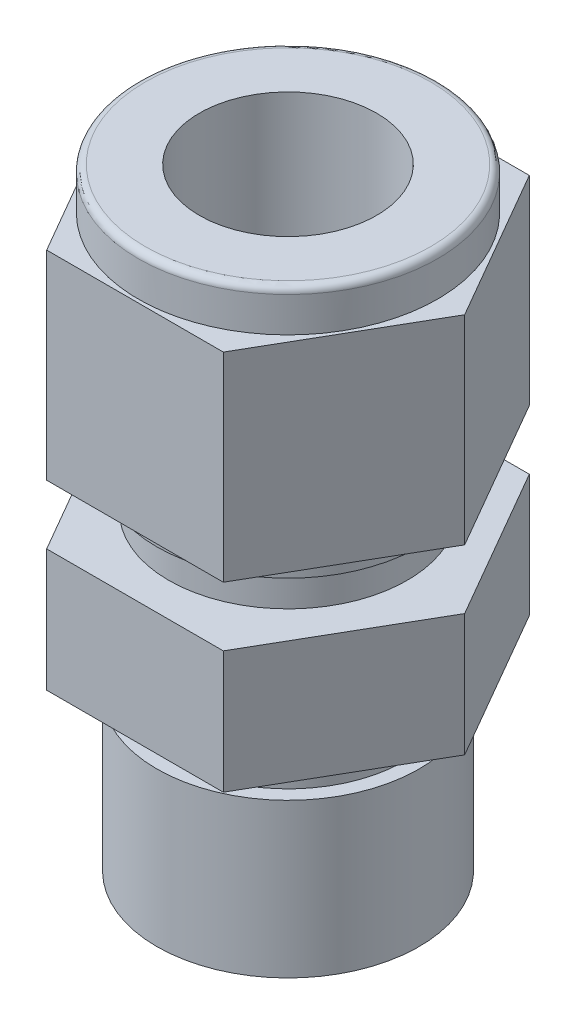
SolidWorks part; units mm, degrees
ref_plane "Front Plane" through (0, 0, 0) normal (0, 0, 1) x (1, 0, 0)
ref_plane "Top Plane" through (0, 0, 0) normal (0, 1, 0) x (1, 0, 0)
ref_plane "Right Plane" through (0, 0, 0) normal (1, 0, 0) x (0, 0, -1)
sketch "Sketch1" plane through (0, 0, 0) normal (0, 1, 0) x (1, 0, 0)
  circle A0 centre (0, 0) radius 9.525
  dimension "D1" = 19.05
extrude "Boss-Extrude1" add sketch "Sketch1" along normal blind 11.176
sketch "Sketch3" plane through (0, 11.176, 0) normal (0, 1, 0) x (1, 0, 0)
  circle A0 centre (0, 0) radius 8.509
  dimension "D1" = 17.018
extrude "Boss-Extrude3" add sketch "Sketch3" along normal blind 2.54
sketch "Sketch4" plane through (0, 13.716, 0) normal (0, 1, 0) x (1, 0, 0)
  line L1 (12.8316, 0) -> (6.4158, 11.1125)
  line L2 (6.4158, 11.1125) -> (-6.4158, 11.1125)
  line L3 (-6.4158, 11.1125) -> (-12.8316, 0)
  line L4 (-12.8316, 0) -> (-6.4158, -11.1125)
  line L5 (-6.4158, -11.1125) -> (6.4158, -11.1125)
  line L6 (6.4158, -11.1125) -> (12.8316, 0)
  circle A0 centre (0, 0) radius 11.1125 construction
  dimension "D1" = 22.225
extrude "Boss-Extrude4" add sketch "Sketch4" along normal blind 8.89
sketch "Sketch5" plane through (0, 22.606, 0) normal (0, 1, 0) x (1, 0, 0)
  circle A0 centre (0, 0) radius 8.6614
  dimension "D1" = 17.3228
extrude "Boss-Extrude5" add sketch "Sketch5" along normal blind 2.54
sketch "Sketch6" plane through (0, 25.146, 0) normal (0, 1, 0) x (1, 0, 0)
  circle A0 centre (0, 0) radius 9.525
  dimension "D1" = 19.05
extrude "Boss-Extrude6" add sketch "Sketch6" along normal blind 1.778
sketch "Sketch7" plane through (0, 26.924, 0) normal (0, 1, 0) x (1, 0, 0)
  line L1 (-6.4158, -11.1125) -> (6.4158, -11.1125)
  line L2 (6.4158, -11.1125) -> (12.8316, 0)
  line L3 (12.8316, 0) -> (6.4158, 11.1125)
  line L4 (6.4158, 11.1125) -> (-6.4158, 11.1125)
  line L5 (-6.4158, 11.1125) -> (-12.8316, 0)
  line L6 (-12.8316, 0) -> (-6.4158, -11.1125)
  circle A0 centre (0, 0) radius 11.1125 construction
  dimension "D1" = 22.225
extrude "Boss-Extrude7" add sketch "Sketch7" along normal blind 14.478
sketch "Sketch8" plane through (0, 41.402, 0) normal (0, 1, 0) x (1, 0, 0)
  circle A0 centre (0, 0) radius 10.8712
  dimension "D1" = 21.7424
extrude "Boss-Extrude8" add sketch "Sketch8" along normal blind 3.048
fillet "Fillet1" radius 0.508 1 edges at (0, 44.45, 10.8712)
sketch "Sketch9" plane through (0, 44.45, 0) normal (0, 1, 0) x (1, 0, 0)
  circle A0 centre (0, 0) radius 6.4389
  dimension "D1" = 12.8778
extrude "Cut-Extrude1" cut sketch "Sketch9" against normal through all
